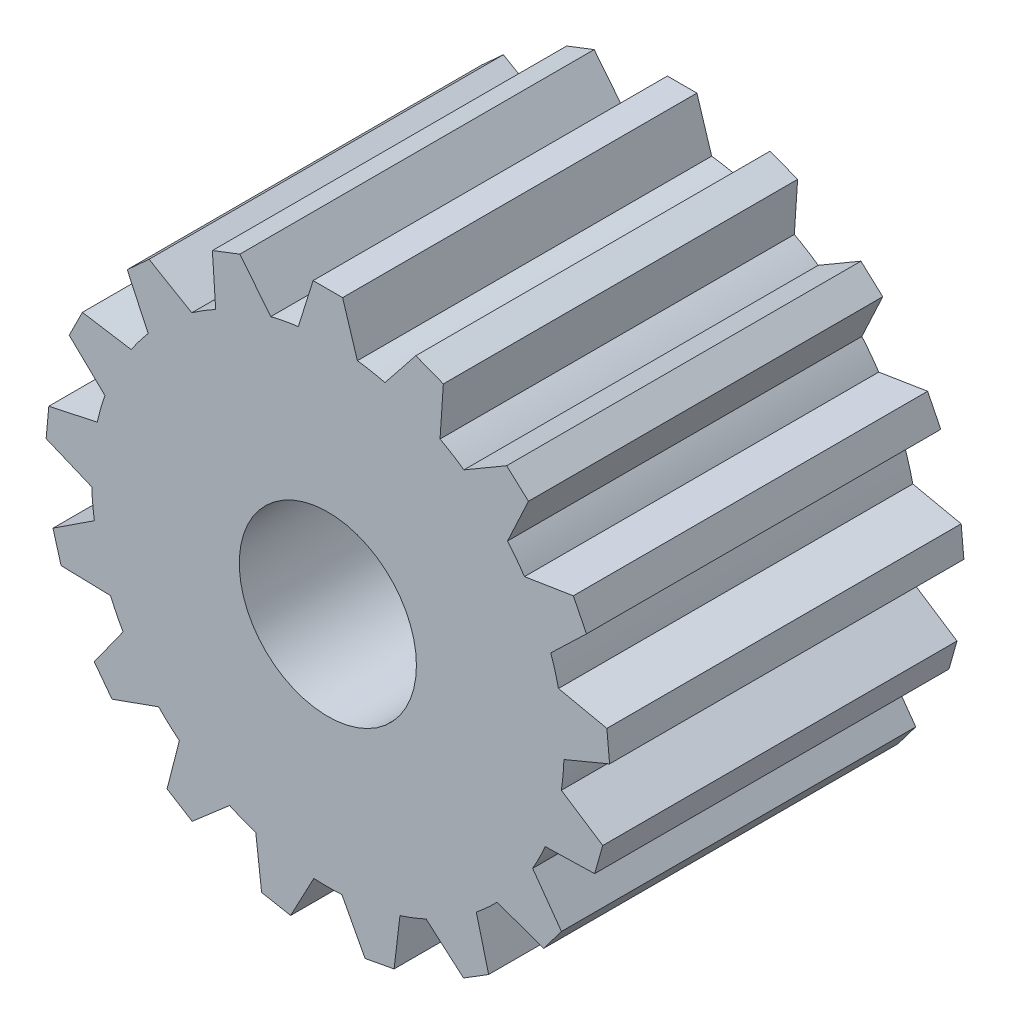
SolidWorks part; units mm, degrees
ref_plane "Front Plane" through (0, 0, 0) normal (0, 0, 1) x (1, 0, 0)
ref_plane "Top Plane" through (0, 0, 0) normal (0, 1, 0) x (1, 0, 0)
ref_plane "Right Plane" through (0, 0, 0) normal (1, 0, 0) x (0, 0, -1)
sketch "Sketch1" plane through (0, 0, 0) normal (0, 0, 1) x (1, 0, 0)
  circle A0 centre (0, 0) radius 4
  dimension "D1" = 8
extrude "Boss-Extrude1" add sketch "Sketch1" along normal blind 6 contours A0
sketch "Sketch3" plane through (0, 0, 0) normal (0, 0, 1) x (1, 0, 0)
  line L0 (0, 0) -> (0, 6.4022) construction
  line L1 (0, 4.7686) -> (0.25, 4.7686)
  line L2 (0.25, 4.7686) -> (0.5, 3.9686)
  line L3 (0.5, 3.9686) -> (-0.5, 3.9686)
  line L4 (-0.5, 3.9686) -> (-0.25, 4.7686)
  line L5 (-0.25, 4.7686) -> (0, 4.7686)
  circle A0 centre (0, 0) radius 4 construction
  dimension "D1" = 0.8
  dimension "D2" = 0.25
  dimension "D3" = 0.25
  dimension "D4" = 1
sketch "Sketch4" plane through (0, 0, 0) normal (0, 1, 0) x (1, 0, 0)
  line L0 (0, -6.6428) -> (0, 0.4527) construction
extrude "Boss-Extrude2" add sketch "Sketch3" along normal blind 6
pattern_circular "CirPattern1" count 17 over 360 about axis through (0, 0, 0) along (0, 0, 1) of "Boss-Extrude2"
sketch "Sketch5" plane through (0, 0, 0) normal (0, 0, 1) x (1, 0, 0)
  circle A0 centre (0, 0) radius 1.5
  dimension "D1" = 3
extrude "Cut-Extrude1" cut sketch "Sketch5" along normal blind 6
